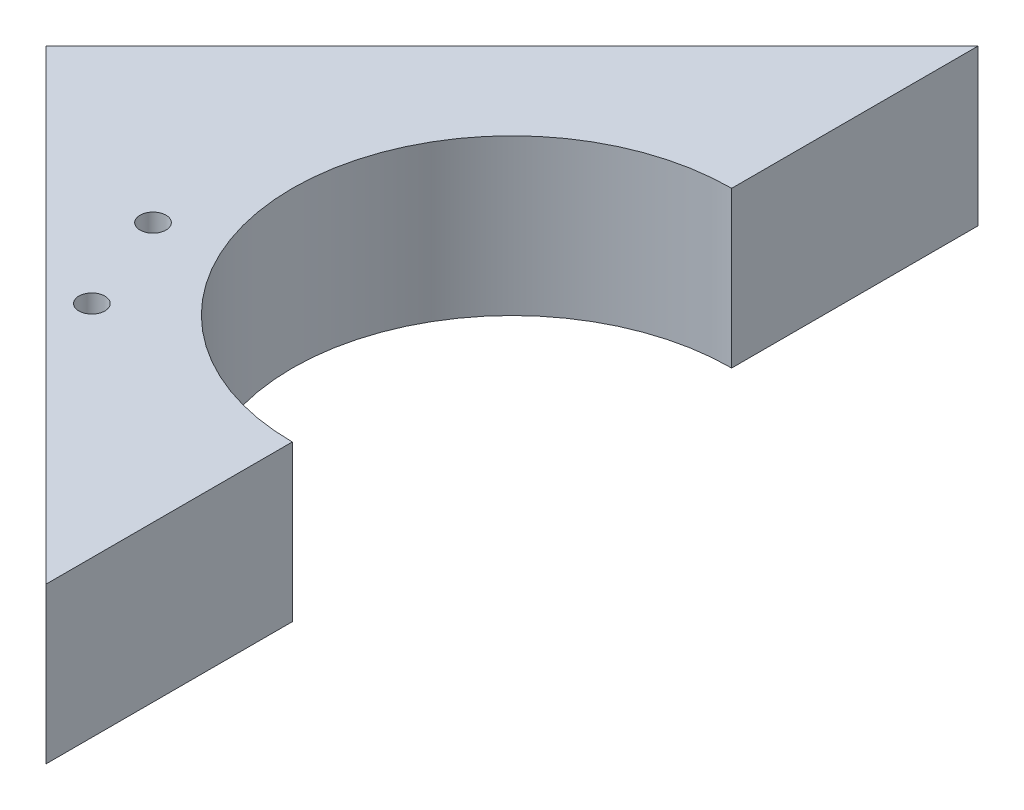
SolidWorks part; units mm, degrees
material "Balsa"
ref_plane "Front Plane" through (0, 0, 0) normal (0, 0, 1) x (1, 0, 0)
ref_plane "Top Plane" through (0, 0, 0) normal (0, 1, 0) x (1, 0, 0)
ref_plane "Right Plane" through (0, 0, 0) normal (1, 0, 0) x (0, 0, -1)
sketch "Sketch1" plane through (0, 0, 0) normal (0, 1, 0) x (1, 0, 0)
  line L0 (0, 0) -> (-107.7631, 107.7631)
  line L1 (-107.7631, 107.7631) -> (0, 215.5261)
  line L2 (0, 56.9631) -> (0, 0)
  line L4 (0, 215.5261) -> (0, 158.5631)
  arc A0 (0, 158.5631) -> (0, 56.9631) centre (0, 107.7631) ccw
  circle A1 centre (-60.0334, 84.7821) radius 3
  circle A2 centre (-50.9026, 61.5092) radius 3
  dimension "D1" = 50
  dimension "D3" = 152.4
  dimension "D5" = 0
  dimension "D6" = 101.6
  dimension "D11" = 17.5
  dimension "D12" = 6
  dimension "D4" = 25
  dimension "D13" = 6
  dimension "D2" = 152.4
  dimension "D7" = 215.5261
  dimension "D8" = 56.9631
  dimension "D9" = 56.9631
  dimension "D10" = 7.5
extrude "Boss-Extrude1" add sketch "Sketch1" along normal blind 36
